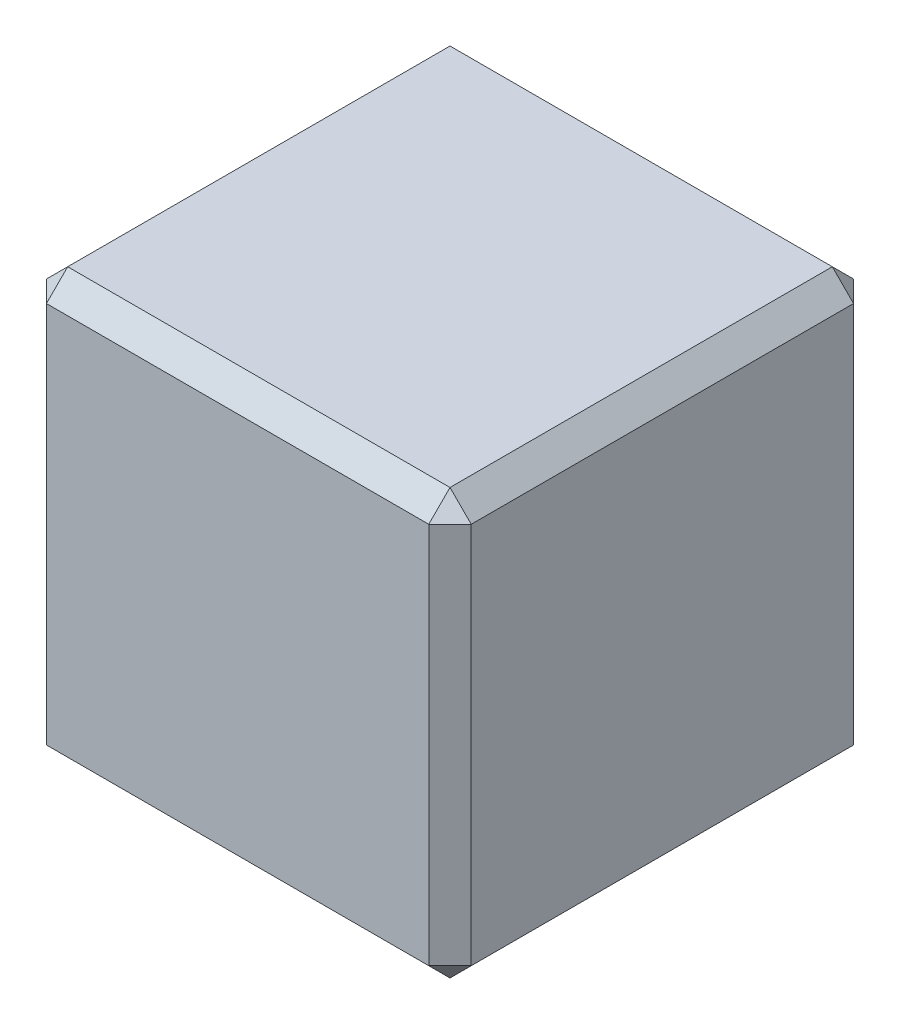
SolidWorks part; units mm, degrees
material "Plain Carbon Steel"
ref_plane "Front Plane" through (0, 0, 0) normal (0, 0, 1) x (1, 0, 0)
ref_plane "Top Plane" through (0, 0, 0) normal (0, 1, 0) x (1, 0, 0)
ref_plane "Right Plane" through (0, 0, 0) normal (1, 0, 0) x (0, 0, -1)
sketch "Sketch1" plane through (0, 0, 0) normal (0, 0, 1) x (1, 0, 0)
  line L1 (0, 0) -> (20, 0)
  line L2 (0, 0) -> (0, 20)
  line L3 (0, 20) -> (20, 20)
  line L4 (20, 0) -> (20, 20)
  dimension "D1" = 20
  dimension "D2" = 20
extrude "Boss-Extrude1" add sketch "Sketch1" along normal blind 20
chamfer "Chamfer1" distance 1 angle 45 12 edges at (0, 0, 10) (10, 0, 0) (0, 10, 0) (20, 0, 10) (20, 10, 0) (20, 10, 20) (10, 0, 20) (0, 10, 20) (20, 20, 10) (10, 20, 20) (0, 20, 10) (10, 20, 0)
